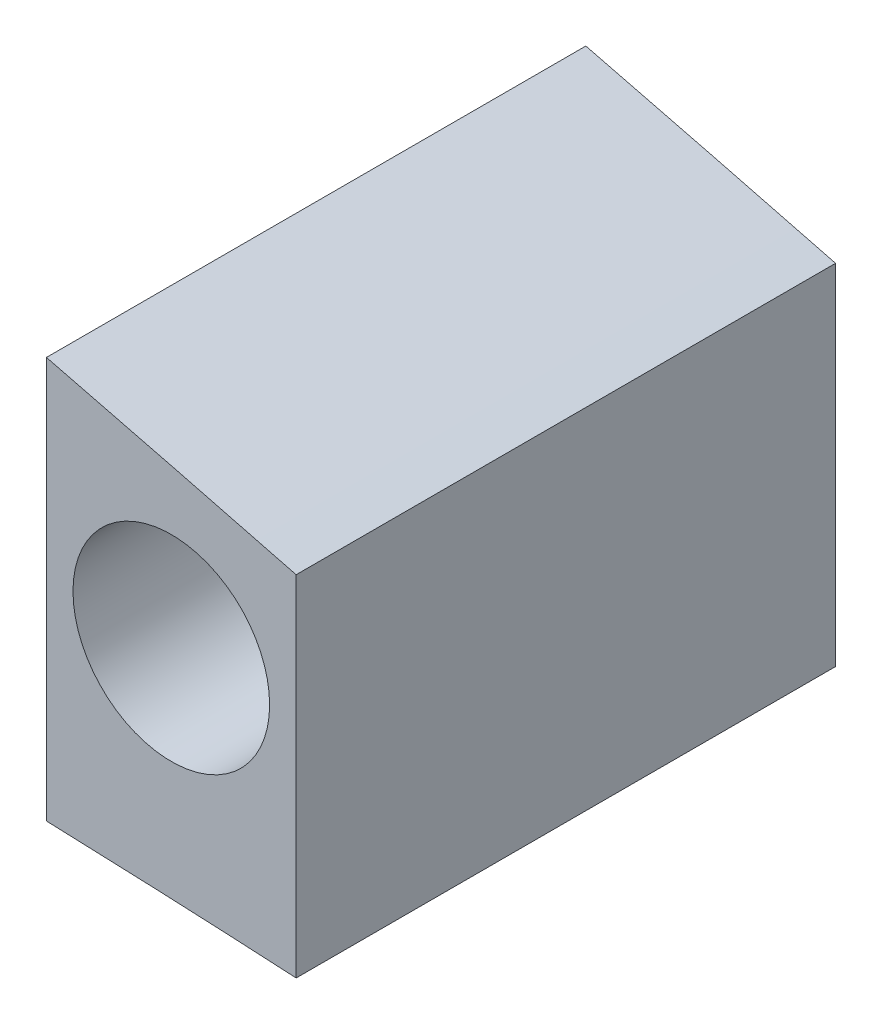
SolidWorks part; units mm, degrees
ref_plane "Front Plane" through (0, 0, 0) normal (0, 0, 1) x (1, 0, 0)
ref_plane "Top Plane" through (0, 0, 0) normal (0, 1, 0) x (1, 0, 0)
ref_plane "Right Plane" through (0, 0, 0) normal (1, 0, 0) x (0, 0, -1)
sketch "Sketch1" plane through (0, 0, 0) normal (0, 0, 1) x (1, 0, 0)
  spline S0 degree 3 poles (0.0006, 0.0001) (0.8106, 7.3592) (8.6491, 17.8566) (26.2867, 29.9752) (52.1111, 42.0692) (89.5976, 49.2908) (131.4008, 47.8848) (173.2567, 40.0411) (217.9611, 29.613) (256.9521, 19.5289) (290.3598, 8.711) (301.2732, 4.3828) (314.8169, -0.5162) (309.8463, 0.0001) knots 0 0 0 0 0.060864 0.113688 0.188609 0.312909 0.448482 0.557612 0.691544 0.852438 0.929756 0.976058 1 1 1 1
  spline S1 degree 3 poles (309.8463, 0.0001) (303.9568, 1.471) (293.9895, 2.094) (276.264, 4.5144) (260.8463, 5.4274) (235.8588, 7.8703) (205.1014, 8.8381) (157.7186, 9.0307) (110.4973, 6.1815) (66.5062, -0.5867) (36.4547, -6.0985) (15.3166, -6.1891) (1.2307, -6.9241) (0.0006, 0.0001) knots 0 0 0 0 0.057787 0.095275 0.171021 0.205339 0.335319 0.464904 0.658702 0.785512 0.893517 0.943092 1 1 1 1
extrude "Boss-Extrude1" add sketch "Sketch1" along normal blind 27.432
sketch "Sketch2" plane through (0, 0, 27.432) normal (0, 0, 1) x (1, 0, 0)
  line L1 (390.8807, -48.3469) -> (233.6463, -48.3469)
  line L2 (390.8807, -48.3469) -> (390.8807, 106.1594)
  line L3 (390.8807, 106.1594) -> (233.6463, 106.1594)
  line L4 (233.6463, -48.3469) -> (233.6463, 106.1594)
  circle A0 centre (20.32, 10.16) radius 6.35
  circle A1 centre (227.2963, 19.0501) radius 5
  dimension "D2" = 12.7
  dimension "D3" = 10
  dimension "D6" = 20.32
  dimension "D1" = 82.55
  dimension "D4" = 19.05
  dimension "D5" = 10.16
  dimension "D7" = 6.35
extrude "Cut-Extrude1" cut sketch "Sketch2" against normal through all
sketch "Sketch3" plane through (0, 0, 27.432) normal (0, 0, 1) x (1, 0, 0)
  line L0 (233.6463, 25.4528) -> (233.6463, 7.6905) construction
  line L1 (-72.2426, 80.4352) -> (220.9463, 80.4352)
  line L2 (-72.2426, 80.4352) -> (-72.2426, -57.5361)
  line L3 (-72.2426, -57.5361) -> (220.9463, -57.5361)
  line L4 (220.9463, 80.4352) -> (220.9463, -57.5361)
  dimension "D1" = 12.7
extrude "Cut-Extrude2" cut sketch "Sketch3" against normal through all
